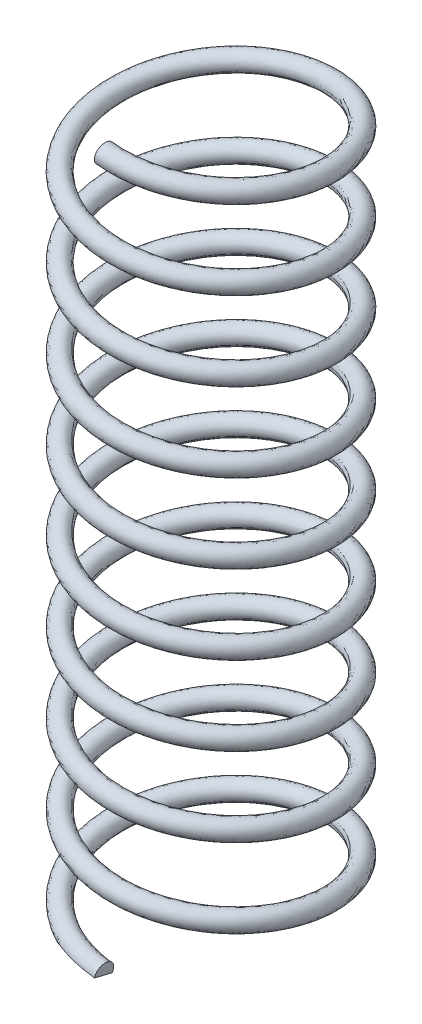
SolidWorks part; units mm, degrees
ref_plane "Plan de face" through (0, 0, 0) normal (0, 0, 1) x (1, 0, 0)
ref_plane "Plan de dessus" through (0, 0, 0) normal (0, 1, 0) x (1, 0, 0)
ref_plane "Plan de droite" through (0, 0, 0) normal (1, 0, 0) x (0, 0, -1)
sketch "Esquisse1" plane through (0, 0, 0) normal (0, 0, 1) x (1, 0, 0)
  circle A0 centre (0, 0) radius 6
  dimension "D1" = 12
sketch "Esquisse2" plane through (0, 0, 0) normal (0, 0, 1) x (1, 0, 0)
  line L0 (67, 0) -> (67, 247.0878) construction
  line L1 (0, 0) -> (134, 0) construction
  dimension "D1" = 134
sketch "Esquisse4" plane through (0, 0, 0) normal (0, 1, 0) x (1, 0, 0)
  line L0 (0, 0) -> (134, 0) construction
  circle A0 centre (67, 0) radius 67
curve "Hélice/Spirale1" pitch 49.4444 height 445 turns 9
sweep "Balayage1" add path "Hélice/Spirale1" circular profile diameter 12 parameters "D3"=12
sketch "Esquisse5" plane through (66.0883, -7.7622, 0) normal (0.9932, -0.1167, 0) x (0, 0, -1)
  line L0 (-74.3411, 8.6655) -> (-61, 5.1274)
  line L1 (-61, 5.1274) -> (-59.9001, 1.2283)
  line L2 (-59.9001, 1.2283) -> (-71.9944, 0.7229)
  line L3 (-71.9944, 0.7229) -> (-74.3411, 8.6655)
extrude "Enlèv. mat.-Extru.1" cut sketch "Esquisse5" against normal blind 30
